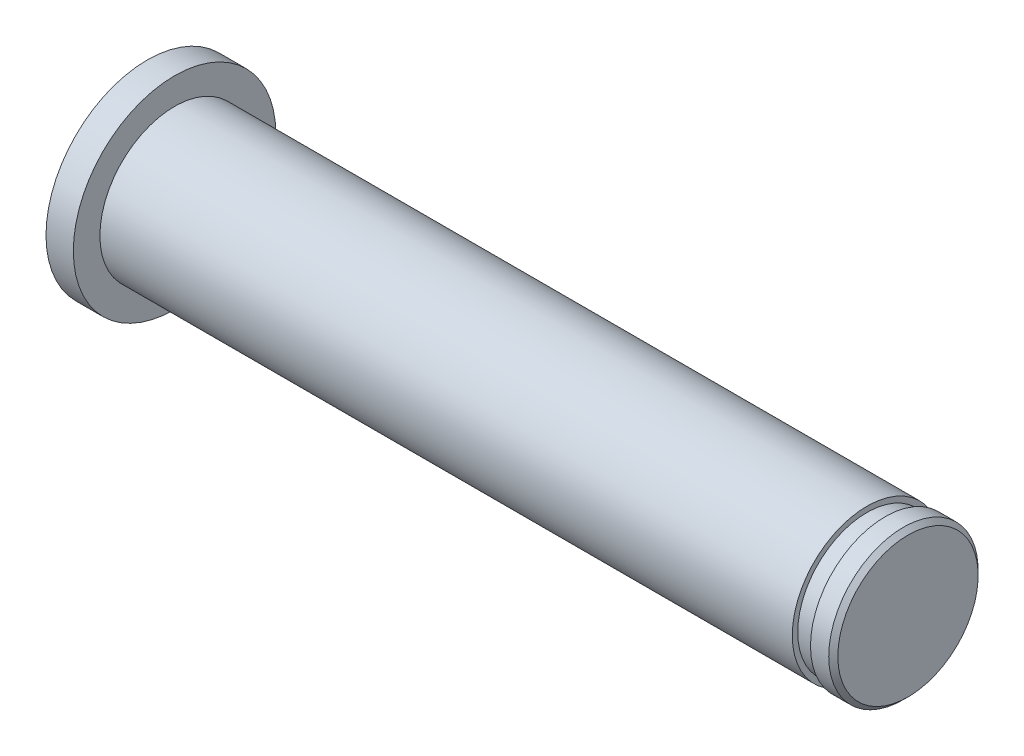
SolidWorks part; units mm, degrees
material "AISI 1045 Acero estirado en frío"
ref_plane "Alzado" through (0, 0, 0) normal (0, 0, 1) x (1, 0, 0)
ref_plane "Planta" through (0, 0, 0) normal (0, 1, 0) x (1, 0, 0)
ref_plane "Vista lateral" through (0, 0, 0) normal (1, 0, 0) x (0, 0, -1)
sketch "Croquis2" plane through (0, 0, 0) normal (0, 0, 1) x (1, 0, 0)
  line L0 (0, 0) -> (83.5, 0) construction
  line L1 (0, 0) -> (0, 11.115)
  line L2 (0, 11.115) -> (3, 11.115)
  line L3 (3, 11.115) -> (3, 8.2)
  line L7 (3, 8.2) -> (79, 8.2)
  line L8 (83, 8.2) -> (81, 8.2)
  line L9 (81, 7.6) -> (81, 8.2)
  line L10 (79, 7.6) -> (81, 7.6)
  line L11 (79, 8.2) -> (79, 7.6)
  line L12 (83.5, 0) -> (83.5, 7.7)
  line L13 (0, 0) -> (83.5, 0)
  line L15 (83.5, 7.7) -> (83, 8.2)
  point P3 (0, 0)
  point P4 (0, 0)
  point P10 (83.5, 8.2)
  dimension "D1" = 3
  dimension "D2" = 11.115
  dimension "D3" = 8.2
  dimension "D4" = 7.6
  dimension "D5" = 2
  dimension "D6" = 76
  dimension "D7" = 2.5
revolve "Revolución1" add sketch "Croquis2" angle 360 about L13
